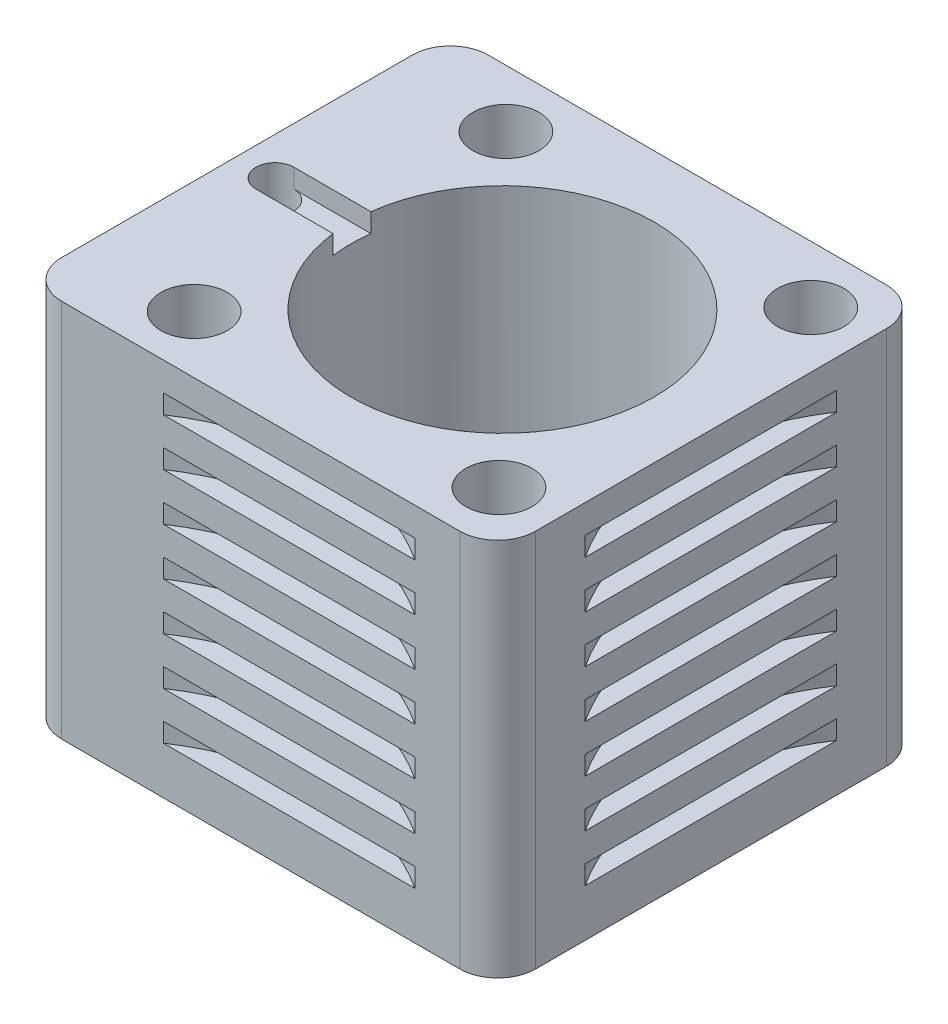
SolidWorks part; units mm, degrees
ref_plane "Front Plane" through (0, 0, 0) normal (0, 0, 1) x (1, 0, 0)
ref_plane "Top Plane" through (0, 0, 0) normal (0, 1, 0) x (1, 0, 0)
ref_plane "Right Plane" through (0, 0, 0) normal (1, 0, 0) x (0, 0, -1)
sketch "Sketch1" plane through (0, 0, 0) normal (0, 1, 0) x (1, 0, 0)
  line L0 (-22, 22.5) -> (-24, 22.5)
  line L1 (18, -22.5) -> (-22, -22.5)
  line L2 (22, -18.5) -> (22, 18.5)
  line L3 (18, 22.5) -> (-22, 22.5)
  line L4 (-22, -22.5) -> (-22, 22.5) construction
  line L5 (22, -22.5) -> (-22, 22.5) construction
  line L6 (22, 22.5) -> (-22, -22.5) construction
  line L7 (-28, 18.5) -> (-28, -18.5)
  line L8 (-24, -22.5) -> (-22, -22.5)
  line L9 (-24, 22.5) -> (-24, -22.5) construction
  circle A0 centre (-24, 0) radius 2
  circle A1 centre (16.0797, 16.4452) radius 3.5
  circle A2 centre (-16.0797, 16.4452) radius 3.5
  circle A3 centre (-16.0797, -16.4452) radius 3.5
  circle A4 centre (16.0797, -16.4452) radius 3.5
  circle A5 centre (0, 0) radius 23 construction
  circle A6 centre (0, 0) radius 16
  arc A7 (-24, 22.5) -> (-28, 18.5) centre (-24, 18.5) ccw
  arc A8 (22, 18.5) -> (18, 22.5) centre (18, 18.5) ccw
  arc A9 (18, -22.5) -> (22, -18.5) centre (18, -18.5) ccw
  arc A10 (-28, -18.5) -> (-24, -22.5) centre (-24, -18.5) ccw
  point P0 (0, 0)
  dimension "D5" = 4
  dimension "D6" = 7
  dimension "D7" = 46
  dimension "D8" = 32
  dimension "D9" = 4
  dimension "D1" = 45
  dimension "D2" = 22
  dimension "D3" = 50
  dimension "D4" = 24
extrude "Boss-Extrude1" add sketch "Sketch1" along normal mid plane 40
sketch "Sketch2" plane through (0, -20, 0) normal (0, -1, 0) x (1, 0, 0)
  circle A0 centre (0, 0) radius 16 construction
  circle A1 centre (0, 0) radius 16
  circle A2 centre (0, 0) radius 18
  dimension "D1" = 36
sketch "Sketch3" plane through (0, 20, 0) normal (0, 1, 0) x (1, 0, 0)
  line L1 (-24, 2) -> (-15.8745, 2)
  line L3 (-24, -2) -> (-15.8745, -2)
  circle A0 centre (-24, 0) radius 2 construction
  arc A1 (-24, -2) -> (-24, 2) centre (-24, 0) ccw
  circle A2 centre (0, 0) radius 16 construction
  arc A3 (-15.8745, 2) -> (-15.8745, -2) centre (0, 0) ccw
extrude "Cut-Extrude1" cut sketch "Sketch3" against normal blind 2
sketch "Sketch5" plane through (0, 20, 0) normal (0, 1, 0) x (1, 0, 0)
  line L0 (0, 42.5) -> (0, -42.5) construction
  line L1 (0, 0) -> (42, 0) construction
  line L3 (0, -18.5) -> (0, -42.5)
  line L4 (-28, 22.5) -> (22, 22.5)
  line L5 (-28, 22.5) -> (-28, -22.5)
  line L6 (-28, -22.5) -> (22, -22.5)
  line L7 (22, 22.5) -> (22, -22.5)
  line L8 (0, 18.5) -> (0, 42.5)
  line L9 (42, 0) -> (18, 0)
  circle A0 centre (42, 0) radius 24
  circle A1 centre (0, 42.5) radius 24
  circle A2 centre (0, -42.5) radius 24
  line M13 (-24, -22.5) -> (18, -22.5)
  dimension "D1" = 48
  dimension "D2" = 4
  dimension "D3" = 4
  dimension "D4" = 4
extrude "Cut-Extrude2" cut sketch "Sketch5" against normal blind 2 from offset 3 contours L3 A2 L6 | A2 L3 M13 | L9 A0 L7 | L7 A0 L9 | L8 A1 L4 | L4 A1 L8 offset against normal yes
pattern_linear "LPattern1" count 7 spacing 5 along (0, -1, 0) of "Cut-Extrude2"
extrude "Cut-Extrude3" cut sketch "Sketch2" against normal blind 2
